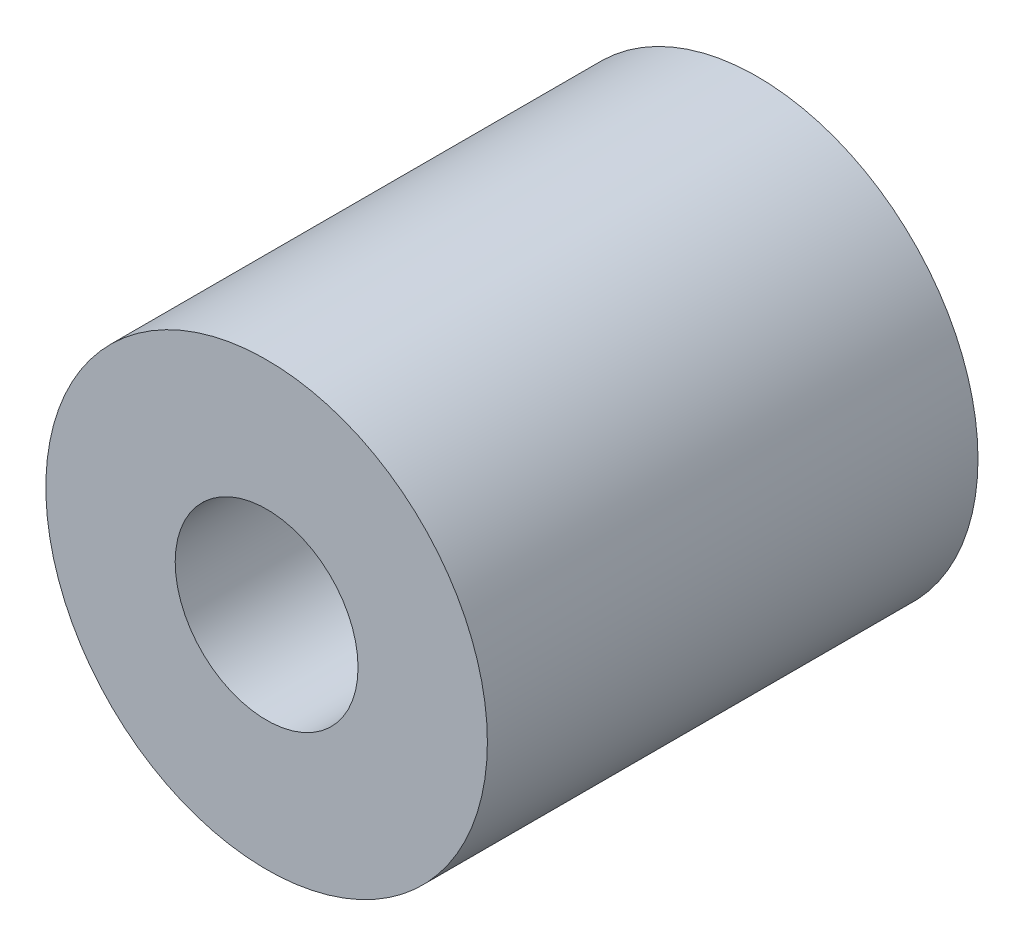
SolidWorks part; units mm, degrees
ref_plane "Plan de face" through (0, 0, 0) normal (0, 0, 1) x (1, 0, 0)
ref_plane "Plan de dessus" through (0, 0, 0) normal (0, 1, 0) x (1, 0, 0)
ref_plane "Plan de droite" through (0, 0, 0) normal (1, 0, 0) x (0, 0, -1)
sketch "Esquisse1" plane through (0, 0, 0) normal (0, 0, 1) x (1, 0, 0)
  circle A0 centre (0, 0) radius 2.05
  circle A1 centre (0, 0) radius 4.95
  dimension "D1" = 4.1
  dimension "D2" = 9.9
extrude "Boss.-Extru.1" add sketch "Esquisse1" along normal blind 11
